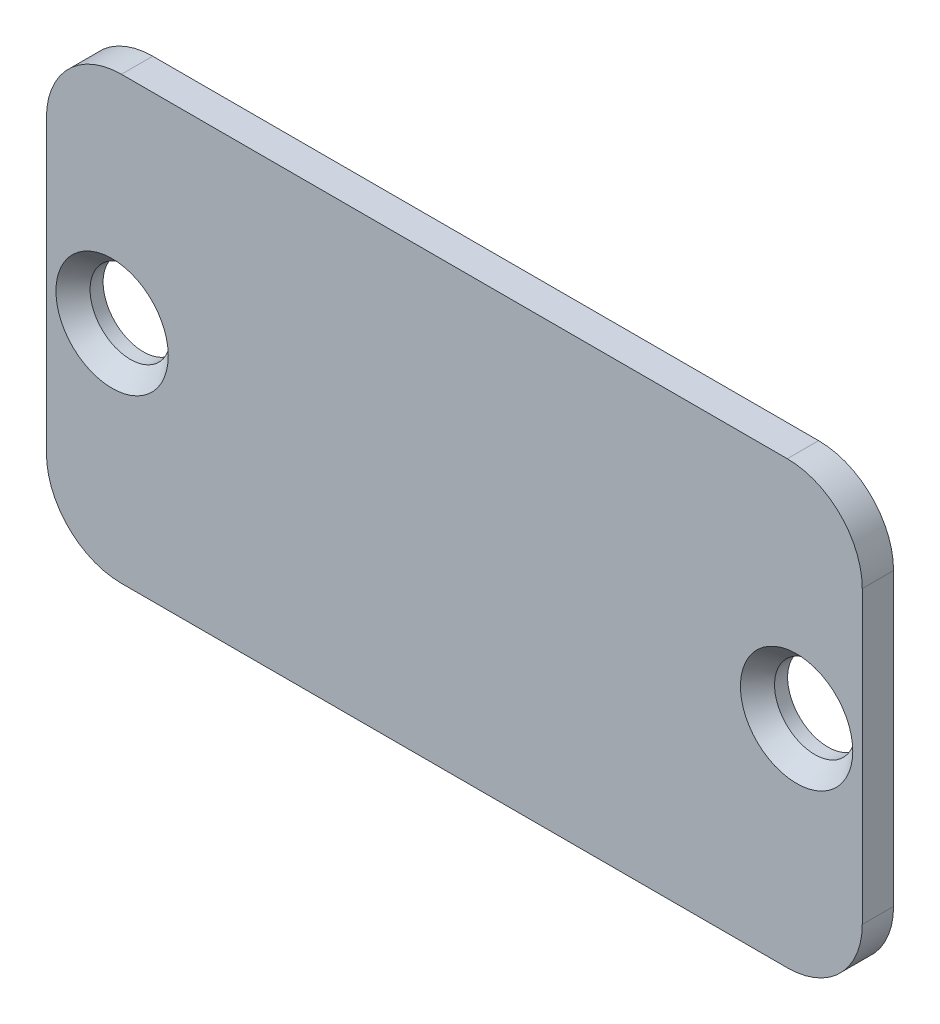
SolidWorks part; units mm, degrees
ref_plane "Front Plane" through (0, 0, 0) normal (0, 0, 1) x (1, 0, 0)
ref_plane "Top Plane" through (0, 0, 0) normal (0, 1, 0) x (1, 0, 0)
ref_plane "Right Plane" through (0, 0, 0) normal (1, 0, 0) x (0, 0, -1)
ref_plane "Plane1" through (0, 0, 31.3998) normal (0, 0, -1) x (-1, 0, 0)
sketch "Sketch1" plane through (0, 0, 31.3998) normal (0, 0, -1) x (-1, 0, 0)
  line L0 (16.9189, 11.465) -> (-17.7111, 11.465)
  line L1 (-21.6111, 7.565) -> (-21.6111, -7.565)
  line L2 (-17.7111, -11.465) -> (16.9189, -11.465)
  line L3 (20.8189, -7.565) -> (20.8189, 7.565)
  arc A0 (20.8189, 7.565) -> (16.9189, 11.465) centre (16.9189, 7.565) ccw
  arc A1 (-17.7111, 11.465) -> (-21.6111, 7.565) centre (-17.7111, 7.565) ccw
  arc A2 (-21.6111, -7.565) -> (-17.7111, -11.465) centre (-17.7111, -7.565) ccw
  arc A3 (16.9189, -11.465) -> (20.8189, -7.565) centre (16.9189, -7.565) ccw
  dimension "D1" = 42.43
extrude "Boss-Extrude1" add sketch "Sketch1" against normal blind 1.6281
hole_wizard "CSK for M3.5 Flat Head Machine Screw1" positions "Sketch3" profile "Sketch2" countersink size "M3.5" standard "ANSI Metric"
sketch "Sketch3" plane through (0, 0, 33.0279) normal (0, 0, 1) x (1, 0, 0)
  point P0 (-17.4039, 0)
  point P1 (18.1961, 0)
sketch "Sketch2" plane through (-17.4039, 0, 33.0279) normal (1, 0, 0) x (0, -1, 0)
  line L0 (0, 0) -> (0, 1.6281)
  line L1 (0, 1.6281) -> (2.0955, 1.6281)
  line L2 (2.0955, 1.6281) -> (2.0955, 0.9496)
  line L3 (2.0955, 0.9496) -> (2.921, 0)
  line L5 (2.921, 0) -> (0, 0)
  line L6 (-2.0955, 0.9496) -> (-2.921, 0) construction
  line L11 (0, -6.35) -> (0, 107.95) construction
  dimension "Thru Hole Dia." = 4.191
  dimension "Thru Hole Depth" = 1.6281
  dimension "Near C'Sink Dia." = 5.842
  dimension "Near C'Sink Angle" = 82
